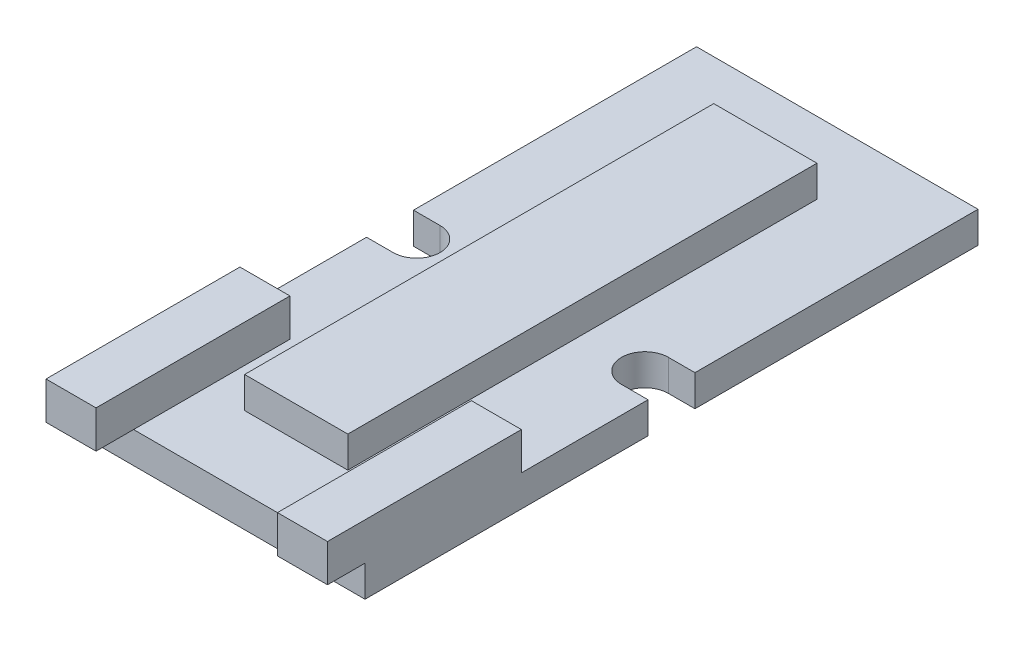
SolidWorks part; units mm, degrees
ref_plane "Front Plane" through (0, 0, 0) normal (0, 0, 1) x (1, 0, 0)
ref_plane "Top Plane" through (0, 0, 0) normal (0, 1, 0) x (1, 0, 0)
ref_plane "Right Plane" through (0, 0, 0) normal (1, 0, 0) x (0, 0, -1)
sketch "Sketch1" plane through (0, 0, 0) normal (0, 1, 0) x (1, 0, 0)
  line L1 (-4.5, -9.8) -> (4.5, -9.8)
  line L2 (-4.5, -9.8) -> (-4.5, 9.8)
  line L3 (-4.5, 9.8) -> (4.5, 9.8)
  line L4 (4.5, -9.8) -> (4.5, 9.8)
  line L5 (-4.5, -9.8) -> (4.5, 9.8) construction
  line L6 (-4.5, 9.8) -> (4.5, -9.8) construction
  line L7 (-3.65, 0) -> (3.65, 0) construction
  line L8 (-3.65, 0.75) -> (-4.5, 0.75)
  line L9 (-3.65, -0.75) -> (-4.5, -0.75)
  line L10 (3.65, 0.75) -> (4.5, 0.75)
  line L11 (3.65, -0.75) -> (4.5, -0.75)
  circle A0 centre (-3.65, 0) radius 0.75
  circle A1 centre (3.65, 0) radius 0.75
  point P0 (0, 0)
  point P5 (0, 0)
  point P11 (0, 0)
  point P21 (4.5, 0.55)
  point P22 (4.5, -0.95)
  point P23 (0, 0)
  dimension "D5" = 1.5
  dimension "D6" = 1.5
  dimension "D1" = 9
  dimension "D2" = 19.6
  dimension "D3" = 7.3
extrude "Boss-Extrude1" add sketch "Sketch1" along normal blind 1 contours A1 L10 L4 L3 L2 L8 A0 L9 L1 L11
sketch "Sketch2" plane through (0, 1, 0) normal (0, 1, 0) x (1, 0, 0)
  line L0 (0, 7.5) -> (0, -7.5) construction
  line L1 (0, 0) -> (2.9, 0) construction
  line L2 (-1.65, -7.5) -> (1.65, -7.5)
  line L3 (-1.65, -7.5) -> (-1.65, 7.5)
  line L4 (-1.65, 7.5) -> (1.65, 7.5)
  line L5 (1.65, -7.5) -> (1.65, 7.5)
  line L6 (-1.65, -7.5) -> (1.65, 7.5) construction
  line L7 (-1.65, 7.5) -> (1.65, -7.5) construction
  arc A0 (3.65, 0.75) -> (3.65, -0.75) centre (3.65, 0) ccw construction
  point P0 (0, 0)
  point P4 (0, 0)
  dimension "D1" = 15
  dimension "D2" = 3.3
extrude "Boss-Extrude2" add sketch "Sketch2" along normal blind 1
sketch "Sketch3" plane through (0, 1, 0) normal (0, 1, 0) x (1, 0, 0)
  line L0 (0, 0) -> (0, -9.8) construction
  line L1 (-4.5, -9.8) -> (-2.9, -9.8)
  line L2 (-4.5, -9.8) -> (-4.5, -4.8)
  line L3 (-4.5, -4.8) -> (-2.9, -4.8)
  line L4 (-2.9, -9.8) -> (-2.9, -4.8)
  line L5 (-4.5, -9.8) -> (4.5, -9.8) construction
  line L6 (2.9, -9.8) -> (2.9, -4.8)
  line L7 (4.5, -4.8) -> (2.9, -4.8)
  line L8 (4.5, -9.8) -> (4.5, -4.8)
  line L9 (4.5, -9.8) -> (2.9, -9.8)
  dimension "D1" = 1.6
  dimension "D2" = 5
extrude "Boss-Extrude3" add sketch "Sketch3" along normal blind 1.2
sketch "Sketch4" plane through (0, 0, 9.8) normal (0, 0, 1) x (1, 0, 0)
  line L0 (4.5, 2.2) -> (4.5, 0) construction
  line L1 (-4.5, 2.2) -> (-2.9, 2.2)
  line L2 (-4.5, 2.2) -> (-4.5, 1)
  line L3 (-4.5, 1) -> (-2.9, 1)
  line L4 (-2.9, 2.2) -> (-2.9, 1)
  line L5 (2.9, 2.2) -> (4.5, 2.2)
  line L6 (2.9, 2.2) -> (2.9, 1)
  line L7 (2.9, 1) -> (4.5, 1)
  line L8 (4.5, 2.2) -> (4.5, 1)
  line L9 (-2.9, 1) -> (2.9, 1) construction
extrude "Boss-Extrude4" add sketch "Sketch4" along normal blind 1.2
